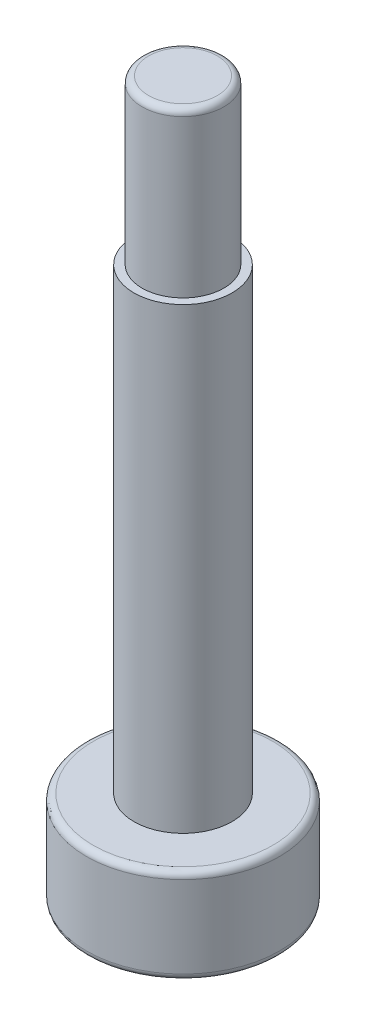
SolidWorks part; units mm, degrees
ref_plane "前视基准面" through (0, 0, 0) normal (0, 0, 1) x (1, 0, 0)
ref_plane "上视基准面" through (0, 0, 0) normal (0, 1, 0) x (1, 0, 0)
ref_plane "右视基准面" through (0, 0, 0) normal (1, 0, 0) x (0, 0, -1)
sketch "草图1" plane through (0, 0, 0) normal (0, 1, 0) x (1, 0, 0)
  circle A0 centre (0, 0) radius 2.95
  dimension "D1" = 5.9
extrude "凸台-拉伸1" add sketch "草图1" along normal blind 2.9
sketch "草图2" plane through (0, 2.9, 0) normal (0, 1, 0) x (1, 0, 0)
  circle A0 centre (0, 0) radius 1.5
  dimension "D1" = 3
extrude "凸台-拉伸2" add sketch "草图2" along normal blind 14
sketch "草图3" plane through (0, 16.9, 0) normal (0, 1, 0) x (1, 0, 0)
  circle A0 centre (0, 0) radius 1.25
  dimension "D1" = 2.5
extrude "凸台-拉伸3" add sketch "草图3" along normal blind 5
sketch "草图4" plane through (0, 0, 0) normal (0, -1, 0) x (1, 0, 0)
  line L1 (2.2473, -0.532) -> (1.5844, 1.6802)
  line L2 (1.5844, 1.6802) -> (-0.6629, 2.2122)
  line L3 (-0.6629, 2.2122) -> (-2.2473, 0.532)
  line L4 (-2.2473, 0.532) -> (-1.5844, -1.6802)
  line L5 (-1.5844, -1.6802) -> (0.6629, -2.2122)
  line L6 (0.6629, -2.2122) -> (2.2473, -0.532)
  circle A0 centre (0, 0) radius 2 construction
  dimension "D1" = 4
extrude "切除-拉伸1" cut sketch "草图4" against normal blind 2
fillet "圆角1" radius 0.2 3 edges at (0, 0, 2.95) (0, 2.9, 2.95) (0, 21.9, 1.25)
